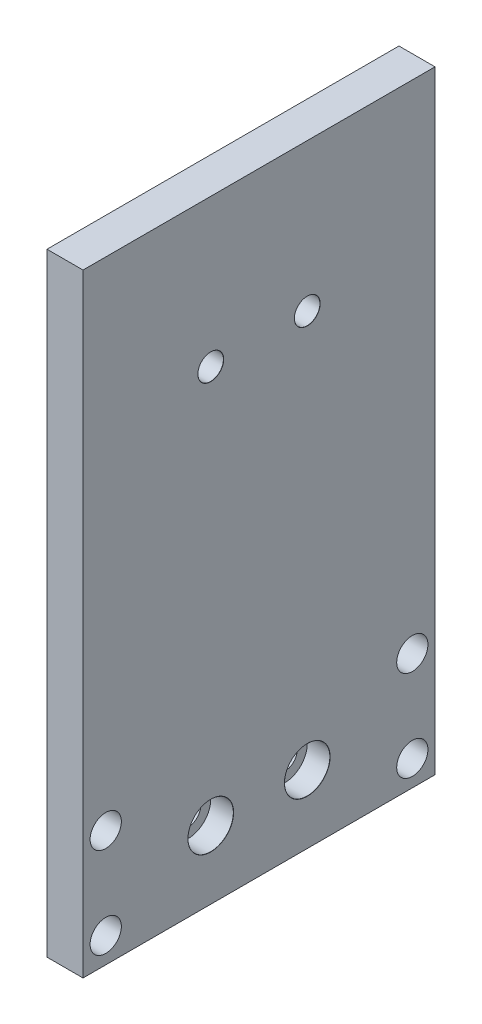
SolidWorks part; units mm, degrees
material "6061 Alloy"
ref_plane "Front" through (0, 0, 0) normal (0, 0, 1) x (1, 0, 0)
ref_plane "Top" through (0, 0, 0) normal (0, 1, 0) x (1, 0, 0)
ref_plane "Right" through (0, 0, 0) normal (1, 0, 0) x (0, 0, -1)
sketch "Sketch1" plane through (0, 0, 0) normal (1, 0, 0) x (0, 0, -1)
  line L1 (0, 0) -> (62, 0)
  line L2 (0, 0) -> (0, 108)
  line L3 (0, 108) -> (62, 108)
  line L4 (62, 0) -> (62, 108)
  dimension "D1" = 62
  dimension "D2" = 108
extrude "Boss-Extrude1" add sketch "Sketch1" along normal blind 6.35
hole_wizard "M5 Clearance Hole1" positions "Sketch2" profile "Sketch3" hole size "M5" standard "ANSI Metric" end condition through all
sketch "Sketch2" plane through (0, 0, 0) normal (-1, 0, 0) x (0, 0, 1)
  line L0 (-58, 4.5) -> (-4, 4.5) construction
  line L2 (-31, 4.5) -> (-31, 0) construction
  line L3 (0, 0) -> (-62, 0) construction
  point P0 (-4, 20.5)
  point P2 (-4, 4.5)
  point P4 (-58, 4.5)
  point P6 (-58, 20.5)
  point P24 (0, 0)
  dimension "D1" = 54
  dimension "D2" = 16
  dimension "D3" = 4.5
sketch "Sketch3" plane through (0, 20.5, -4) normal (0, 1, 0) x (0, 0, 1)
  line L0 (0, 0) -> (0, 6.35)
  line L1 (0, 6.35) -> (2.75, 6.35)
  line L2 (2.75, 6.35) -> (2.75, 0.021)
  line L3 (2.75, 0.021) -> (2.775, 0)
  line L5 (2.775, 0) -> (0, 0)
  line L6 (-2.75, 0.021) -> (-2.775, 0) construction
  line L11 (0, -6.35) -> (0, 107.95) construction
  dimension "Thru Hole Dia." = 5.5
  dimension "Thru Hole Depth" = 6.35
  dimension "Near C'Sink Dia." = 5.55
  dimension "Near C'Sink Angle" = 100
hole_wizard "M4 Clearance Hole1" positions "Sketch4" profile "Sketch5" hole size "M4" standard "ANSI Metric" end condition through all
sketch "Sketch4" plane through (6.35, 0, 0) normal (1, 0, 0) x (0, 0, -1)
  line L0 (0, 0) -> (62, 0) construction
  line L1 (22.5, 82) -> (39.5, 82) construction
  line L3 (31, 82) -> (31, 108) construction
  line L4 (62, 108) -> (0, 108) construction
  point P0 (39.5, 82)
  point P2 (22.5, 82)
  dimension "D1" = 82
  dimension "D2" = 17
sketch "Sketch5" plane through (6.35, 82, -39.5) normal (0, 1, 0) x (0, 0, -1)
  line L0 (0, 0) -> (0, 6.35)
  line L1 (0, 6.35) -> (2.25, 6.35)
  line L2 (2.25, 6.35) -> (2.25, 0.021)
  line L3 (2.25, 0.021) -> (2.275, 0)
  line L5 (2.275, 0) -> (0, 0)
  line L6 (-2.25, 0.021) -> (-2.275, 0) construction
  line L11 (0, -6.35) -> (0, 107.95) construction
  dimension "Thru Hole Dia." = 4.5
  dimension "Thru Hole Depth" = 6.35
  dimension "Near C'Sink Dia." = 4.55
  dimension "Near C'Sink Angle" = 100
hole_wizard "CBORE for M4 SHCS1" positions "Sketch6" profile "Sketch7" counterbore size "M4" standard "ANSI Metric" end condition through all
sketch "Sketch6" plane through (6.35, 0, 0) normal (1, 0, 0) x (0, 0, -1)
  line L0 (0, 0) -> (62, 0) construction
  line L1 (22.5, 12) -> (39.5, 12) construction
  line L3 (31, 12) -> (31, 0) construction
  point P0 (22.5, 12)
  point P2 (39.5, 12)
  point P15 (0, 0)
  dimension "D1" = 12
  dimension "D2" = 17
sketch "Sketch7" plane through (6.35, 12, -22.5) normal (0, 1, 0) x (0, 0, -1)
  line L0 (0, 0) -> (0, 6.35)
  line L1 (0, 6.35) -> (2.25, 6.35)
  line L3 (2.25, 6.35) -> (2.25, 4)
  line L4 (4, 4) -> (2.25, 4)
  line L5 (4, 4) -> (4, 0.021)
  line L6 (4, 0.021) -> (4.025, 0)
  line L7 (4.025, 0) -> (0, 0)
  line L8 (-4, 0.021) -> (-4.025, 0) construction
  line L11 (0, -6.35) -> (0, 107.95) construction
  dimension "Thru Hole Dia." = 4.5
  dimension "Thru Hole Depth" = 6.35
  dimension "C'Bore Dia." = 8
  dimension "C'Bore Depth" = 4
  dimension "Near C'Sink Dia." = 8.05
  dimension "Near C'Sink Angle" = 100
